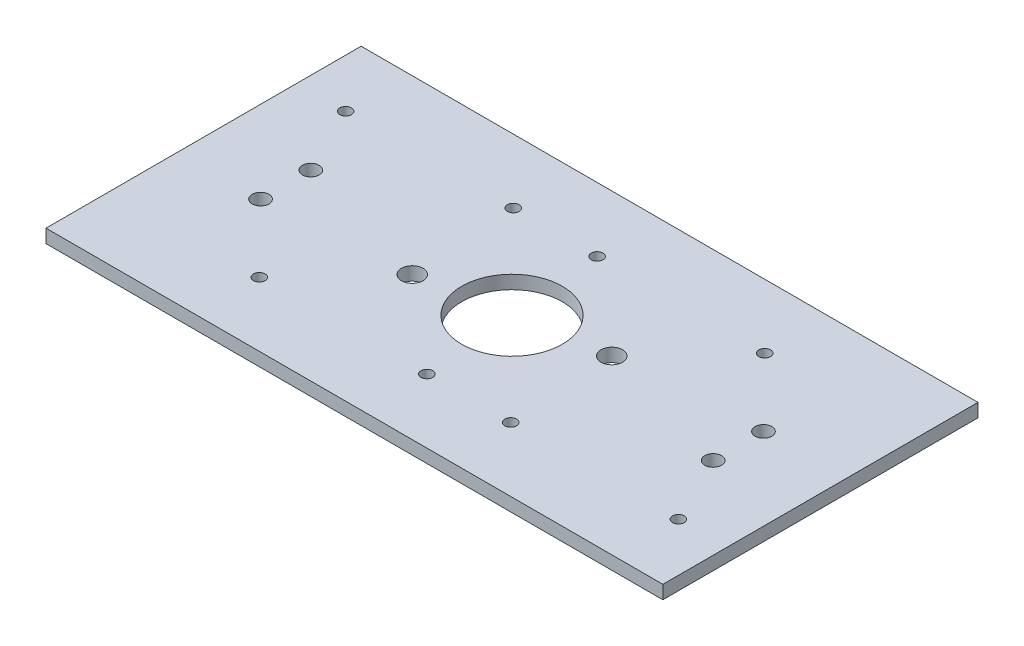
SolidWorks part; units mm, degrees
ref_plane "Front Plane" through (0, 0, 0) normal (0, 0, 1) x (1, 0, 0)
ref_plane "Top Plane" through (0, 0, 0) normal (0, 1, 0) x (1, 0, 0)
ref_plane "Right Plane" through (0, 0, 0) normal (1, 0, 0) x (0, 0, -1)
sketch "Sketch1" plane through (0, 0, 0) normal (0, 1, 0) x (1, 0, 0)
  line L0 (-77.5, 27.88) -> (58.9808, 27.88) construction
  line L1 (-92, -47) -> (92, -47)
  line L2 (-92, -47) -> (-92, 47)
  line L3 (-92, 47) -> (92, 47)
  line L4 (92, -47) -> (92, 47)
  line L5 (-92, -47) -> (92, 47) construction
  line L6 (-92, 47) -> (92, -47) construction
  line L7 (-25.4, 4.36) -> (25.4, 4.36) construction
  line L8 (-67.5, 7.5) -> (86.7249, 7.5) construction
  circle A0 centre (0, 0) radius 15
  circle A1 centre (-2.5, 27.88) radius 1.75
  circle A2 centre (-27.5, 27.88) radius 1.75
  circle A3 centre (47.5, 27.88) radius 1.75
  circle A4 centre (-77.5, 27.88) radius 1.75
  circle A5 centre (25.4, 4.36) radius 3.225
  circle A7 centre (-67.5, 7.5) radius 2.5
  circle A8 centre (67.5, 7.5) radius 2.5
  circle A9 centre (77.5, -27.88) radius 1.75
  circle A10 centre (27.5, -27.88) radius 1.75
  circle A11 centre (2.5, -27.88) radius 1.75
  circle A12 centre (-47.5, -27.88) radius 1.75
  circle A13 centre (-25.4, -4.36) radius 3.225
  circle A14 centre (-67.5, -7.5) radius 2.5
  circle A15 centre (67.5, -7.5) radius 2.5
  point P0 (0, 0)
  point P27 (0, 0)
  point P42 (0, 0)
  dimension "D6" = 3.5
  dimension "D7" = 3.5
  dimension "D8" = 3.5
  dimension "D9" = 3.5
  dimension "D10" = 5
  dimension "D11" = 5
  dimension "D12" = 6.45
  dimension "D13" = 2
  dimension "D20" = 30
  dimension "D1" = 184
  dimension "D2" = 94
  dimension "D3" = 27.88
  dimension "D4" = 7.5
  dimension "D5" = 4.36
  dimension "D14" = 50
  dimension "D15" = 14.5
  dimension "D16" = 25
  dimension "D17" = 50
  dimension "D18" = 25.4
  dimension "D21" = 67.5
  dimension "D22" = 67.5
extrude "Boss-Extrude1" add sketch "Sketch1" along normal blind 4
